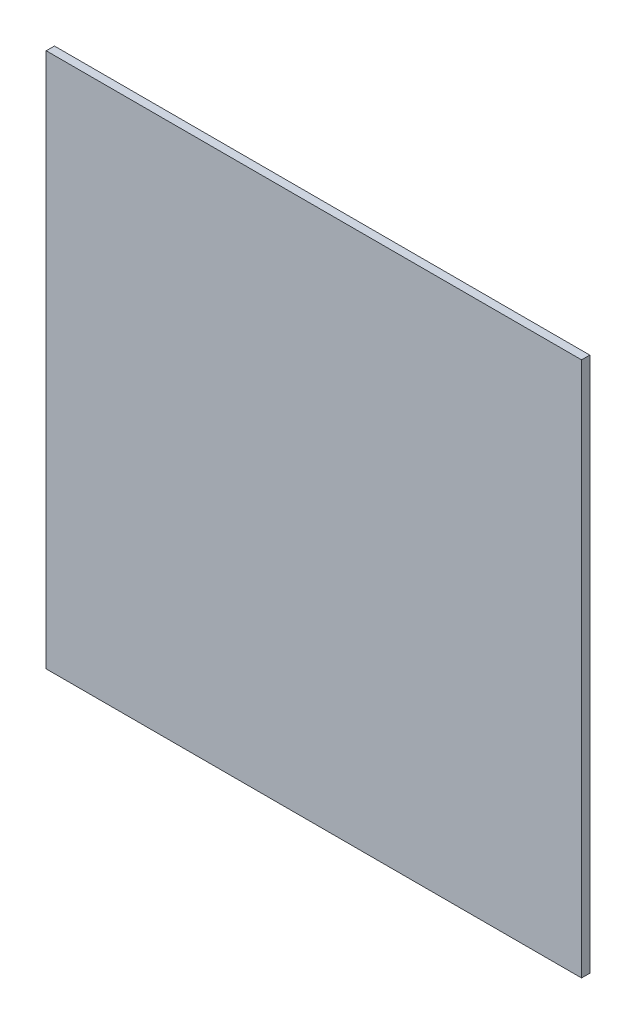
SolidWorks part; units mm, degrees
ref_plane "Plano frontal" through (0, 0, 0) normal (0, 0, 1) x (1, 0, 0)
ref_plane "Plano superior" through (0, 0, 0) normal (0, 1, 0) x (1, 0, 0)
ref_plane "Plano direito" through (0, 0, 0) normal (1, 0, 0) x (0, 0, -1)
sketch "Esboço1" plane through (0, 0, 0) normal (0, 0, 1) x (1, 0, 0)
  line L1 (-17.7021, 18.1862) -> (14.7979, 18.1862)
  line L2 (-17.7021, 18.1862) -> (-17.7021, -14.3138)
  line L3 (-17.7021, -14.3138) -> (14.7979, -14.3138)
  line L4 (14.7979, 18.1862) -> (14.7979, -14.3138)
  dimension "D1" = 32.5
  dimension "D2" = 32.5
extrude "Ressalto-extrusão1" add sketch "Esboço1" along normal blind 0.5
